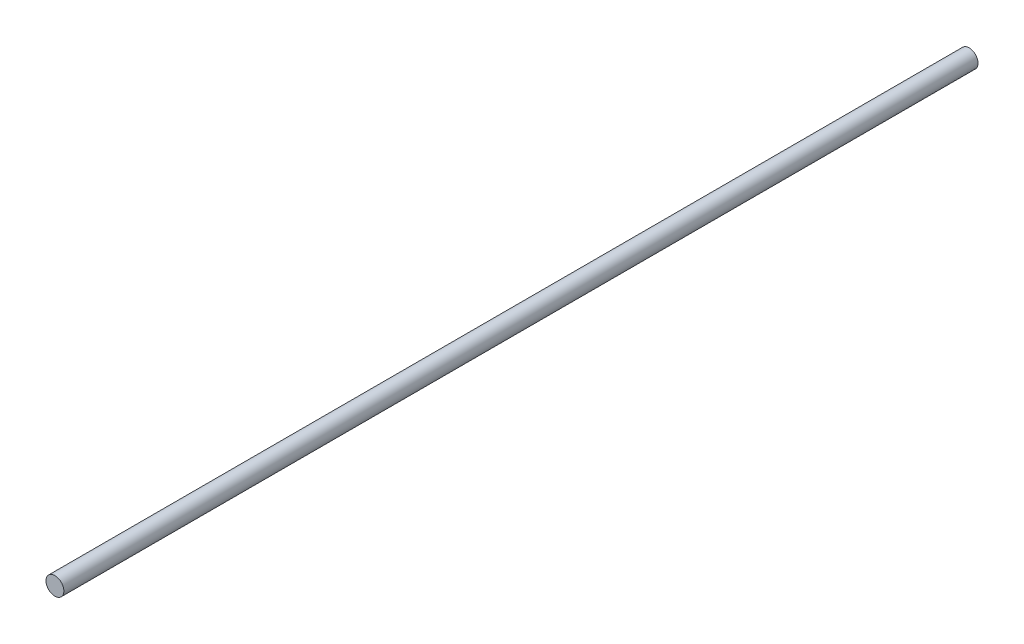
SolidWorks part; units mm, degrees
ref_plane "Front Plane" through (0, 0, 0) normal (0, 0, 1) x (1, 0, 0)
ref_plane "Top Plane" through (0, 0, 0) normal (0, 1, 0) x (1, 0, 0)
ref_plane "Right Plane" through (0, 0, 0) normal (1, 0, 0) x (0, 0, -1)
sketch "Sketch1" plane through (0, 0, 0) normal (0, 0, 1) x (1, 0, 0)
  circle A0 centre (0, 0) radius 5
extrude "Boss-Extrude1" add sketch "Sketch1" along normal blind 512
